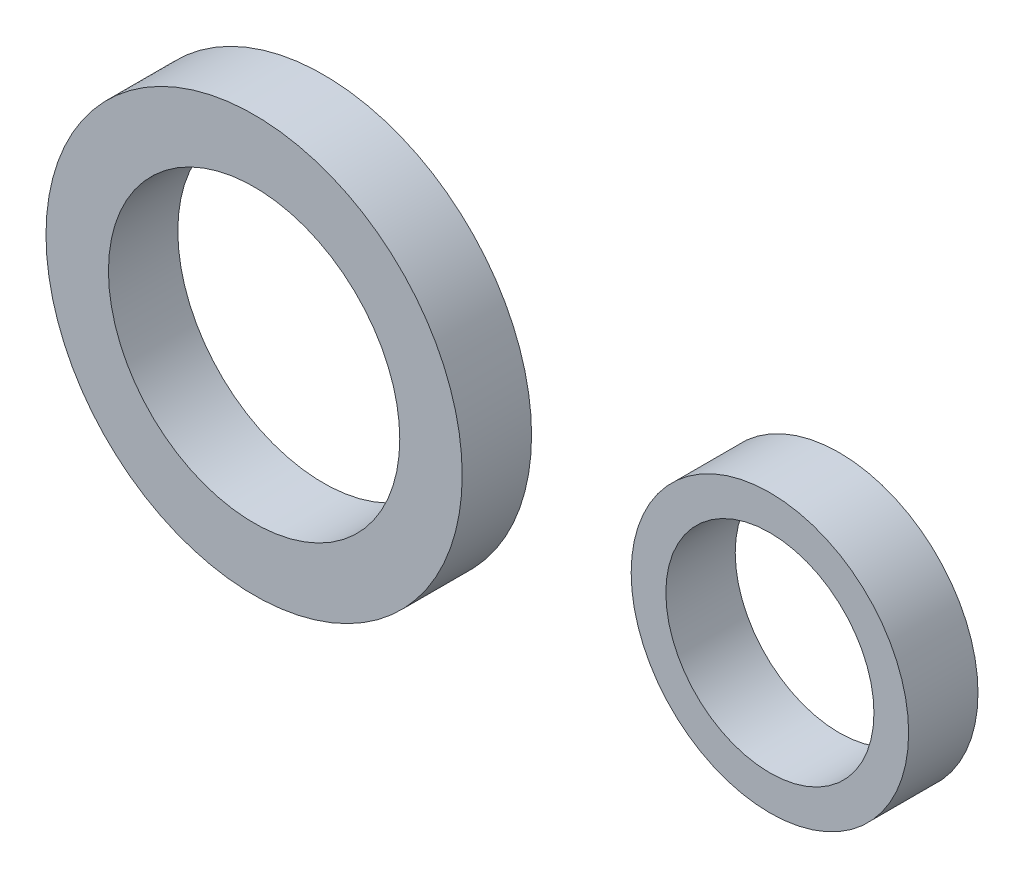
SolidWorks part; units mm, degrees
ref_plane "Plan de face" through (0, 0, 0) normal (0, 0, 1) x (1, 0, 0)
ref_plane "Plan de dessus" through (0, 0, 0) normal (0, 1, 0) x (1, 0, 0)
ref_plane "Plan de droite" through (0, 0, 0) normal (1, 0, 0) x (0, 0, -1)
sketch "Esquisse1" plane through (0, 0, 0) normal (0, 0, 1) x (1, 0, 0)
  circle A0 centre (0, 0) radius 15
  circle A1 centre (0, 0) radius 10.5
extrude "Boss.-Extru.1" add sketch "Esquisse1" along normal blind 5 contours A0
sketch "Esquisse3" plane through (0, 0, 0) normal (0, 0, 1) x (1, 0, 0)
  circle A0 centre (37.1782, 0) radius 10
  circle A1 centre (37.1782, 0) radius 7.5
extrude "Boss.-Extru.2" add sketch "Esquisse3" along normal blind 5 separate body contours A0 | A1
